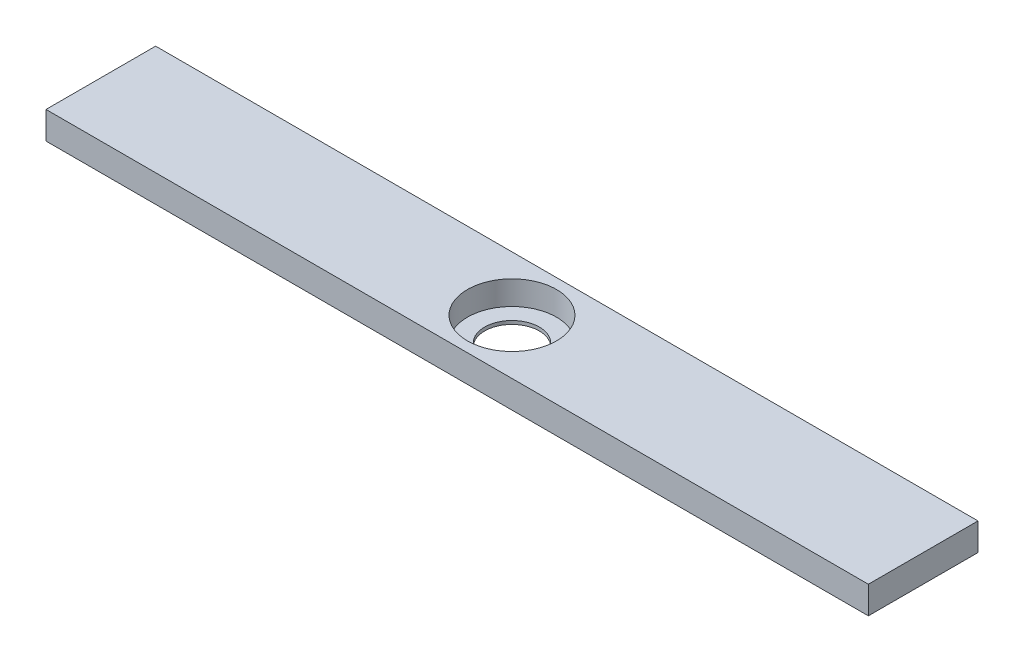
SolidWorks part; units mm, degrees
material "6061-T6 (SS)"
ref_plane "Front Plane" through (0, 0, 0) normal (0, 0, 1) x (1, 0, 0)
ref_plane "Top Plane" through (0, 0, 0) normal (0, 1, 0) x (1, 0, 0)
ref_plane "Right Plane" through (0, 0, 0) normal (1, 0, 0) x (0, 0, -1)
sketch "Sketch1" plane through (0, 0, 0) normal (0, 1, 0) x (1, 0, 0)
  line L1 (-190.5, 25.4) -> (190.5, 25.4)
  line L2 (-190.5, 25.4) -> (-190.5, -25.4)
  line L3 (-190.5, -25.4) -> (190.5, -25.4)
  line L4 (190.5, 25.4) -> (190.5, -25.4)
  line L5 (-190.5, 25.4) -> (190.5, -25.4) construction
  line L6 (-190.5, -25.4) -> (190.5, 25.4) construction
  point P0 (0, 0)
  dimension "D1" = 381
  dimension "D2" = 50.8
extrude "Boss-Extrude1" add sketch "Sketch1" along normal blind 12.7
sketch "Sketch2" plane through (0, 12.7, 0) normal (0, 1, 0) x (1, 0, 0)
  circle A0 centre (0, 0) radius 20.6375
  dimension "D1" = 41.275
extrude "Cut-Extrude1" cut sketch "Sketch2" against normal blind 11.1125
sketch "Sketch3" plane through (0, 1.5875, 0) normal (0, 1, 0) x (1, 0, 0)
  circle A0 centre (0, 0) radius 12.7
  dimension "D1" = 25.4
extrude "Cut-Extrude2" cut sketch "Sketch3" against normal through all
